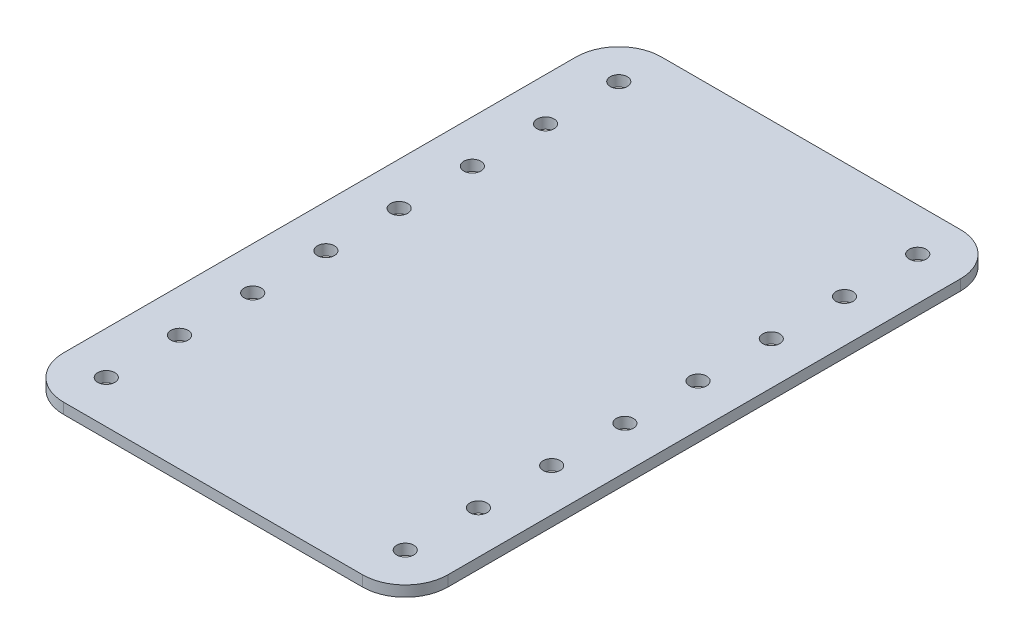
SolidWorks part; units mm, degrees
ref_plane "Front Plane" through (0, 0, 0) normal (0, 0, 1) x (1, 0, 0)
ref_plane "Top Plane" through (0, 0, 0) normal (0, 1, 0) x (1, 0, 0)
ref_plane "Right Plane" through (0, 0, 0) normal (1, 0, 0) x (0, 0, -1)
sketch "Sketch1" plane through (0, 0, 0) normal (0, 1, 0) x (1, 0, 0)
  line L1 (-57.15, -88.9) -> (57.15, -88.9)
  line L2 (-57.15, -88.9) -> (-57.15, 88.9)
  line L3 (-57.15, 88.9) -> (57.15, 88.9)
  line L4 (57.15, -88.9) -> (57.15, 88.9)
  line L5 (-57.15, -88.9) -> (57.15, 88.9) construction
  line L6 (-57.15, 88.9) -> (57.15, -88.9) construction
  point P0 (0, 0)
  dimension "D1" = 114.3
  dimension "D2" = 177.8
extrude "Boss-Extrude1" add sketch "Sketch1" along normal blind 3.175
sketch "Sketch2" plane through (0, 3.175, 0) normal (0, 1, 0) x (1, 0, 0)
  line L0 (57.15, 88.9) -> (-57.15, 88.9) construction
  line L1 (-57.15, 88.9) -> (-57.15, -88.9) construction
  line L2 (-57.15, -88.9) -> (57.15, -88.9) construction
  line L3 (0, 0) -> (0, 28.6343) construction
  circle A0 centre (-44.45, 76.2) radius 2.54
  circle A1 centre (-44.45, 54.4286) radius 2.54
  circle A2 centre (-44.45, 32.6571) radius 2.54
  circle A3 centre (-44.45, 10.8857) radius 2.54
  circle A4 centre (-44.45, -10.8857) radius 2.54
  circle A5 centre (-44.45, -32.6571) radius 2.54
  circle A6 centre (-44.45, -54.4286) radius 2.54
  circle A7 centre (-44.45, -76.2) radius 2.54
  circle A8 centre (44.45, -76.2) radius 2.54
  circle A9 centre (44.45, -54.4286) radius 2.54
  circle A10 centre (44.45, -32.6571) radius 2.54
  circle A11 centre (44.45, -10.8857) radius 2.54
  circle A12 centre (44.45, 10.8857) radius 2.54
  circle A13 centre (44.45, 32.6571) radius 2.54
  circle A14 centre (44.45, 54.4286) radius 2.54
  circle A15 centre (44.45, 76.2) radius 2.54
  dimension "D1" = 5.08
  dimension "D2" = 12.7
  dimension "D3" = 12.7
  dimension "D4" = 8
  dimension "D5" = 12.7
extrude "Cut-Extrude1" cut sketch "Sketch2" against normal blind 3.175
fillet "Fillet1" radius 12.7 4 edges at (-57.15, 1.5875, -88.9) (57.15, 1.5875, -88.9) (57.15, 1.5875, 88.9) (-57.15, 1.5875, 88.9)
